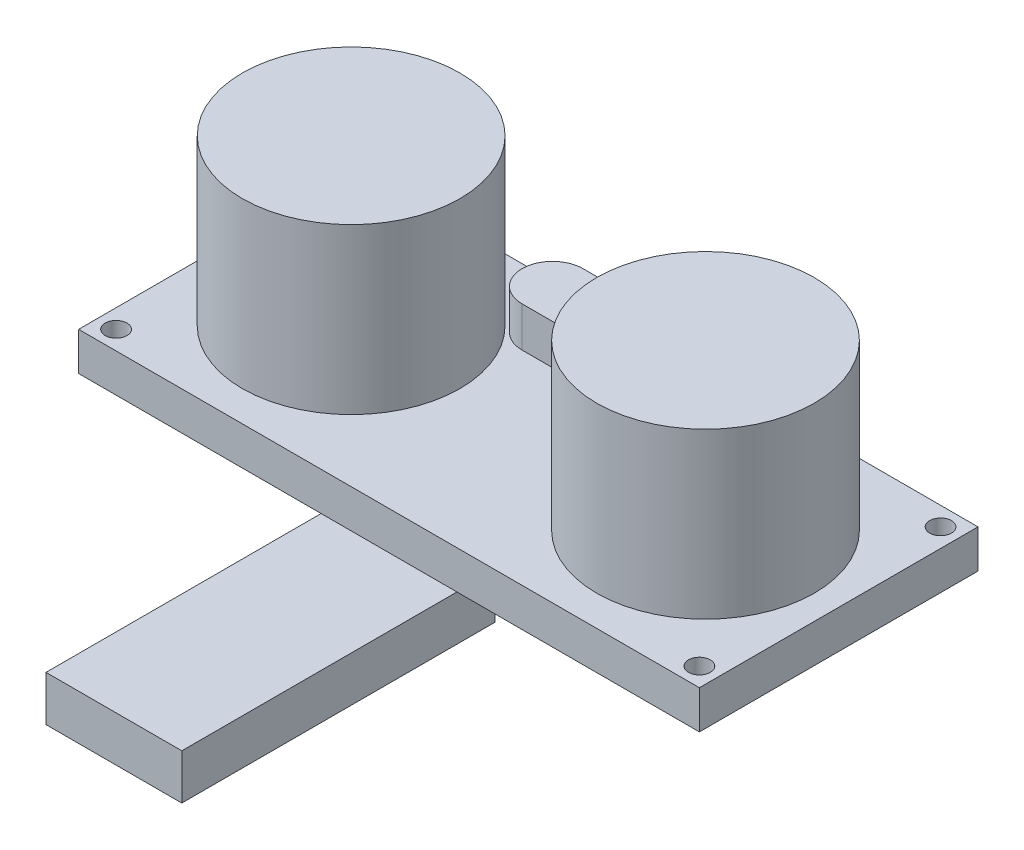
SolidWorks part; units mm, degrees
ref_plane "Front Plane" through (0, 0, 0) normal (0, 0, 1) x (1, 0, 0)
ref_plane "Top Plane" through (0, 0, 0) normal (0, 1, 0) x (1, 0, 0)
ref_plane "Right Plane" through (0, 0, 0) normal (1, 0, 0) x (0, 0, -1)
sketch "Sketch1" plane through (0, 0, 0) normal (0, 1, 0) x (1, 0, 0)
  line L1 (22.6377, -10.16) -> (-22.6378, -10.16)
  line L2 (22.6377, -10.16) -> (22.6377, 10.16)
  line L3 (22.6377, 10.16) -> (-22.6378, 10.16)
  line L4 (-22.6378, -10.16) -> (-22.6378, 10.16)
  line L5 (22.6377, -10.16) -> (-22.6378, 10.16) construction
  line L6 (22.6377, 10.16) -> (-22.6378, -10.16) construction
  point P0 (0, 0)
  dimension "D1" = 20.32
  dimension "D2" = 45.2755
extrude "Boss-Extrude1" add sketch "Sketch1" along normal blind 2.794
sketch "Sketch2" plane through (0, 2.794, 0) normal (0, 1, 0) x (1, 0, 0)
  line L0 (0, 0) -> (0, 10.16) construction
  line L1 (22.6377, 10.16) -> (-22.6378, 10.16) construction
  line L2 (-22.6378, 10.16) -> (-22.6378, -10.16) construction
  circle A0 centre (-12.9223, 0) radius 7.9375
  circle A1 centre (12.9223, 0) radius 7.9375
  dimension "D1" = 15.875
  dimension "D2" = 9.7155
extrude "Boss-Extrude2" add sketch "Sketch2" along normal blind 12.0015
sketch "Sketch3" plane through (0, 2.794, 0) normal (0, 1, 0) x (1, 0, 0)
  line L0 (-5.1564, 6.9215) -> (5.1564, 6.9215) construction
  line L1 (-5.1564, 9.144) -> (5.1564, 9.144)
  line L2 (-5.1564, 4.699) -> (5.1564, 4.699)
  line L3 (22.6377, 10.16) -> (-22.6378, 10.16) construction
  line L4 (22.6377, 10.16) -> (-22.6378, 10.16)
  arc A0 (-5.1564, 9.144) -> (-5.1564, 4.699) centre (-5.1564, 6.9215) ccw
  arc A1 (5.1564, 4.699) -> (5.1564, 9.144) centre (5.1564, 6.9215) ccw
  point P2 (0, 6.9215)
  dimension "D1" = 4.445
  dimension "D2" = 1.016
extrude "Boss-Extrude3" add sketch "Sketch3" along normal blind 2.921
sketch "Sketch5" plane through (0, 0, 0) normal (0, -1, 0) x (1, 0, 0)
  line L0 (-5.1564, -9.144) -> (5.1564, -9.144) construction
  line L1 (-5.1564, -9.144) -> (5.1564, -9.144)
  line L2 (-22.6378, 10.16) -> (22.6377, 10.16) construction
  line L3 (4.953, 7.366) -> (-4.953, 7.366)
  line L4 (4.953, 7.366) -> (4.953, 30.226)
  line L5 (4.953, 30.226) -> (-4.953, 30.226)
  line L6 (-4.953, 7.366) -> (-4.953, 30.226)
  point P6 (0, 7.366)
  point P7 (0, -9.144)
  line M8 (22.6377, 10.16) -> (-22.6378, 10.16)
  dimension "D1" = 9.906
  dimension "D2" = 2.794
  dimension "D3" = 22.86
extrude "Boss-Extrude4" add sketch "Sketch5" along normal blind 3.302 contours L6 L4 L5 M8 | L6 L3 L4 M8
sketch "Sketch6" plane through (0, 2.794, 0) normal (0, 1, 0) x (1, 0, 0)
  line L0 (0, 0) -> (0, 1.937) construction
  line L1 (0, 1.937) -> (0, 0) construction
  line L2 (0, 0) -> (-2.8629, 0) construction
  line L3 (22.6377, 10.16) -> (-22.6378, 10.16) construction
  line L4 (-22.6378, 10.16) -> (-22.6378, -10.16) construction
  circle A0 centre (-21.2725, 8.7948) radius 0.7937
  circle A1 centre (-21.2725, -8.7948) radius 0.7937
  circle A2 centre (21.2725, -8.7948) radius 0.7937
  circle A3 centre (21.2725, 8.7948) radius 0.7937
  dimension "D1" = 1.5875
  dimension "D2" = 1.3652
  dimension "D3" = 1.3652
extrude "Cut-Extrude1" cut sketch "Sketch6" against normal through all
